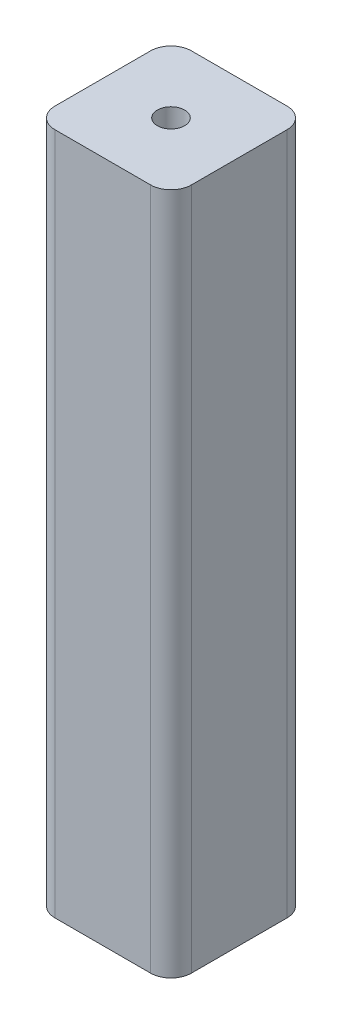
SolidWorks part; units mm, degrees
ref_plane "Front Plane" through (0, 0, 0) normal (0, 0, 1) x (1, 0, 0)
ref_plane "Top Plane" through (0, 0, 0) normal (0, 1, 0) x (1, 0, 0)
ref_plane "Right Plane" through (0, 0, 0) normal (1, 0, 0) x (0, 0, -1)
sketch "Sketch1" plane through (0, 0, 0) normal (0, 1, 0) x (1, 0, 0)
  line L1 (10, -10) -> (-10, -10)
  line L2 (10, -10) -> (10, 10)
  line L3 (10, 10) -> (-10, 10)
  line L4 (-10, -10) -> (-10, 10)
  line L5 (10, -10) -> (-10, 10) construction
  line L6 (10, 10) -> (-10, -10) construction
  point P0 (0, 0)
  dimension "D1" = 20
extrude "Boss-Extrude1" add sketch "Sketch1" along normal blind 100
fillet "Fillet1" radius 3 4 edges at (10, 50, -10) (10, 50, 10) (-10, 50, 10) (-10, 50, -10)
sketch "Sketch2" plane through (0, 100, 0) normal (0, 1, 0) x (1, 0, 0)
  point P0 (0, 0)
  point P1 (0, 0)
sketch "Sketch4" plane through (0, 100, 0) normal (0, 1, 0) x (1, 0, 0)
  circle A0 centre (0, 0) radius 2
  dimension "D1" = 4
extrude "Cut-Extrude1" cut sketch "Sketch4" against normal blind 10 contours A0
ref_plane "Plane1" through (0, 50, 0) normal (0, 1, 0) x (1, 0, 0)
mirror "Mirror1" about plane through (0, 50, 0) normal (0, 1, 0) of "Cut-Extrude1"
